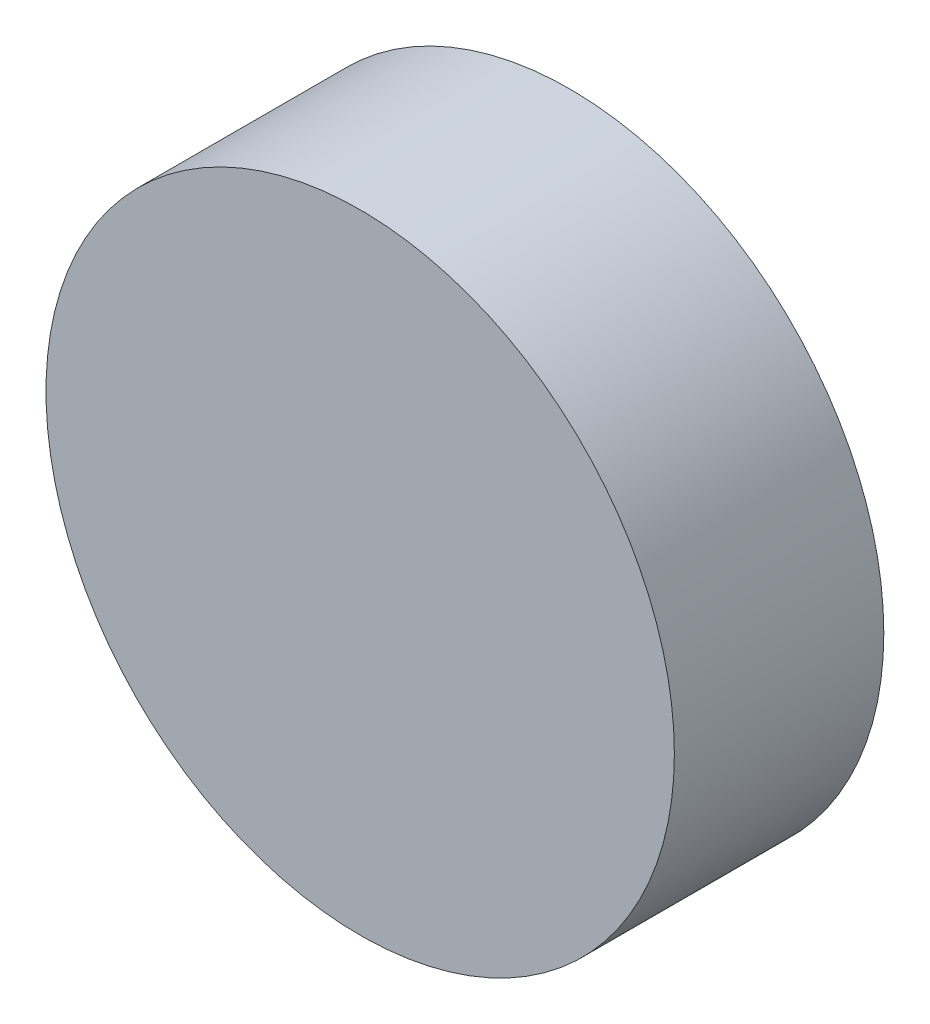
SolidWorks part; units mm, degrees
ref_plane "前视基准面" through (0, 0, 0) normal (0, 0, 1) x (1, 0, 0)
ref_plane "上视基准面" through (0, 0, 0) normal (0, 1, 0) x (1, 0, 0)
ref_plane "右视基准面" through (0, 0, 0) normal (1, 0, 0) x (0, 0, -1)
sketch "草图1" plane through (0, 0, 0) normal (0, 0, 1) x (1, 0, 0)
  circle A0 centre (0, 0) radius 6
  dimension "D1" = 12
extrude "凸台-拉伸1" add sketch "草图1" along normal blind 4 contours A0
